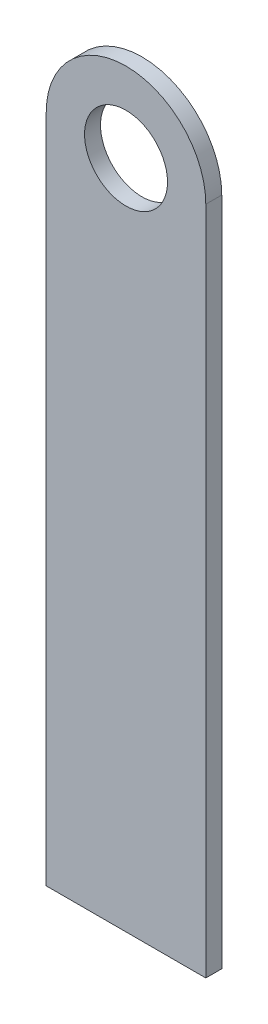
SolidWorks part; units mm, degrees
ref_plane "Front Plane" through (0, 0, 0) normal (0, 0, 1) x (1, 0, 0)
ref_plane "Top Plane" through (0, 0, 0) normal (0, 1, 0) x (1, 0, 0)
ref_plane "Right Plane" through (0, 0, 0) normal (1, 0, 0) x (0, 0, -1)
sketch "Sketch1" plane through (0, 0, 0) normal (0, 0, 1) x (1, 0, 0)
  line L0 (0, 0) -> (0, 210)
  line L1 (50, 210) -> (50, 0)
  line L2 (50, 0) -> (0, 0)
  arc A0 (0, 210) -> (50, 210) centre (25, 210) cw
  circle A1 centre (25, 210) radius 13
  dimension "D3" = 25
  dimension "D4" = 26
  dimension "D1" = 50
  dimension "D2" = 210
extrude "Boss-Extrude1" add sketch "Sketch1" along normal blind 5
